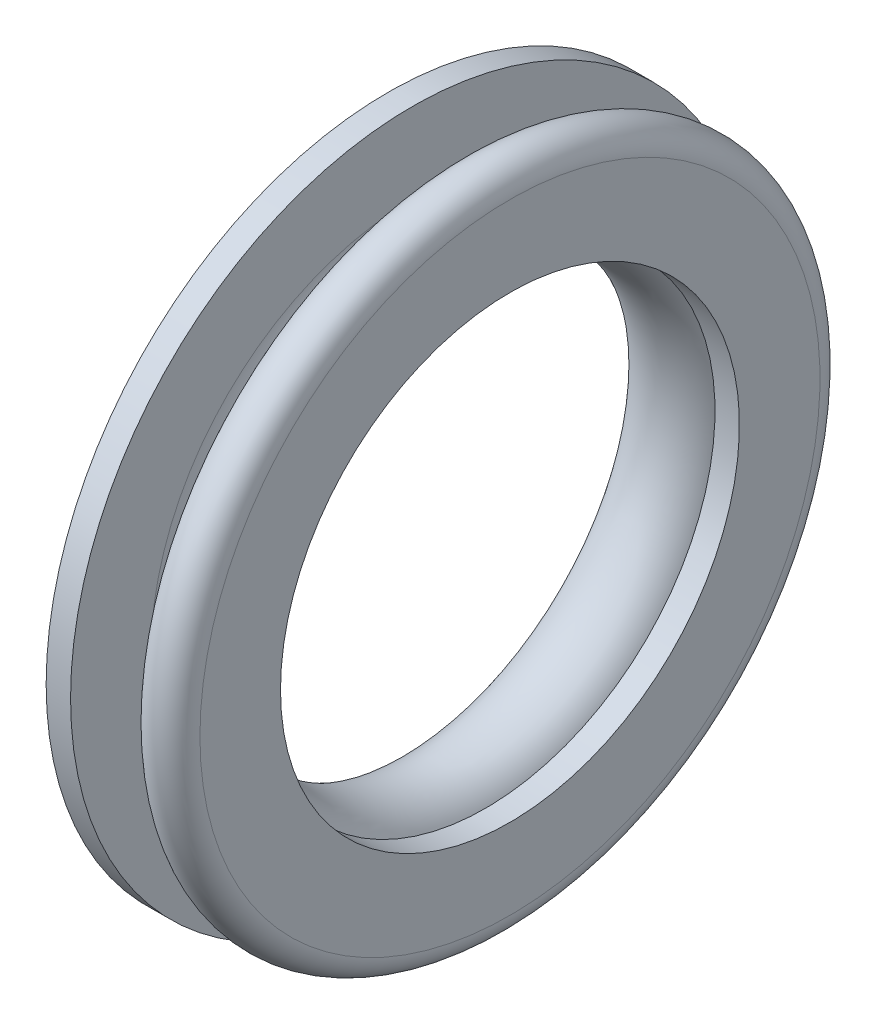
SolidWorks part; units mm, degrees
ref_plane "Front Plane" through (0, 0, 0) normal (0, 0, 1) x (1, 0, 0)
ref_plane "Top Plane" through (0, 0, 0) normal (0, 1, 0) x (1, 0, 0)
ref_plane "Right Plane" through (0, 0, 0) normal (1, 0, 0) x (0, 0, -1)
sketch "Sketch1" plane through (0, 0, 0) normal (0, 0, 1) x (1, 0, 0)
  line L0 (0, 1.65) -> (0, 0)
  line L1 (2, 0) -> (2, 1) construction
  line L2 (2.5, 1) -> (2.5, -0.65)
  line L3 (0.5, 1.65) -> (0.5, 0)
  line L4 (2, 1) -> (2, -0.65)
  line L5 (2.5, -0.65) -> (2, -0.65)
  line L6 (1.5, 0) -> (1.5, 1)
  line L8 (0.5, 1.65) -> (0, 1.65)
  line L9 (0, 1.65) -> (0, -5.35) construction
  line L10 (0, -5.35) -> (4.6505, -5.35) construction
  arc A0 (0, 0) -> (2, 0) centre (1, 0) ccw
  arc A1 (1.5, 1) -> (2.5, 1) centre (2, 1) cw
  arc A2 (0.5, 0) -> (1.5, 0) centre (1, 0) ccw
  dimension "D1" = 1.65
  dimension "D4" = 1
  dimension "D5" = 0.5
  dimension "D2" = 1
  dimension "D3" = 1.65
  dimension "D8" = 0.5
  dimension "D9" = 7
  dimension "D6" = 0.5
  dimension "D7" = 0.5
revolve "Revolve1" add sketch "Sketch1" angle 360 about L10
